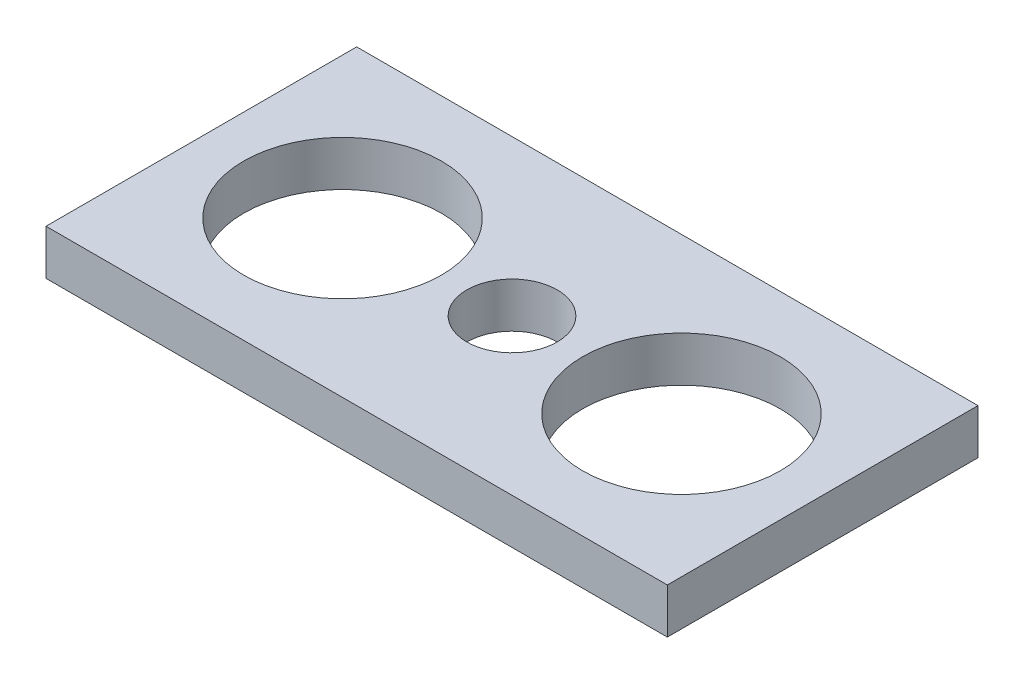
SolidWorks part; units mm, degrees
material "1060 Alloy"
ref_plane "Front Plane" through (0, 0, 0) normal (0, 0, 1) x (1, 0, 0)
ref_plane "Top Plane" through (0, 0, 0) normal (0, 1, 0) x (1, 0, 0)
ref_plane "Right Plane" through (0, 0, 0) normal (1, 0, 0) x (0, 0, -1)
sketch "Sketch2" plane through (0, 0, 0) normal (0, 1, 0) x (1, 0, 0)
  line L1 (0, 0) -> (220, 0)
  line L2 (0, 0) -> (0, 110)
  line L3 (0, 110) -> (220, 110)
  line L4 (220, 0) -> (220, 110)
  circle A0 centre (50, 55) radius 35
  circle A1 centre (170, 55) radius 35
  circle A2 centre (110, 55) radius 16
  dimension "D5" = 70
  dimension "D8" = 70
  dimension "D10" = 32
  dimension "D1" = 220
  dimension "D2" = 110
  dimension "D3" = 55
  dimension "D4" = 50
  dimension "D6" = 50
  dimension "D7" = 55
  dimension "D9" = 110
extrude "Boss-Extrude1" add sketch "Sketch2" along normal blind 16
